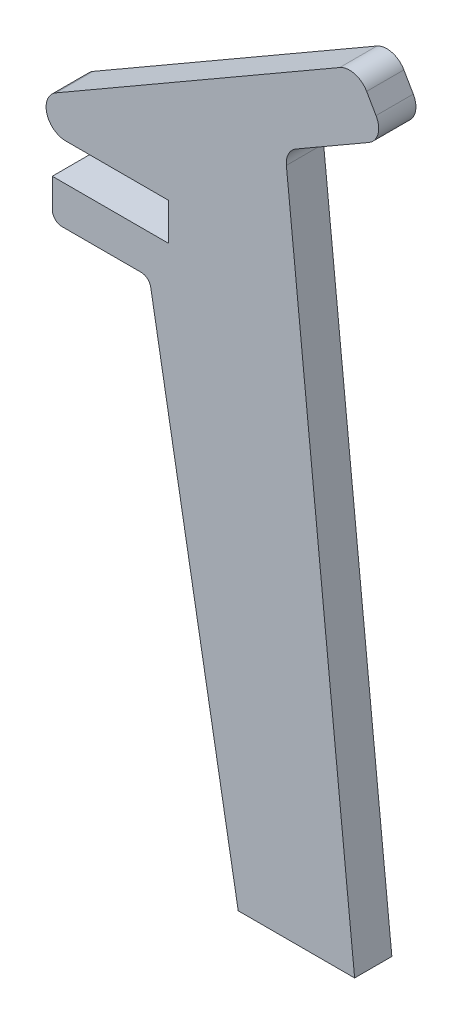
SolidWorks part; units mm, degrees
ref_plane "Front Plane" through (0, 0, 0) normal (0, 0, 1) x (1, 0, 0)
ref_plane "Top Plane" through (0, 0, 0) normal (0, 1, 0) x (1, 0, 0)
ref_plane "Right Plane" through (0, 0, 0) normal (1, 0, 0) x (0, 0, -1)
sketch "Sketch1" plane through (0, 0, 0) normal (0, 0, 1) x (1, 0, 0)
  line L0 (159.9956, -85.9179) -> (150.4706, -69.4202) construction
  line L1 (127, -104.9679) -> (159.9956, -85.9179) construction
  line L2 (150.4706, -69.4202) -> (31.146, -138.3122) construction
  line L3 (-88.9, -138.3122) -> (88.9, -138.3122) construction
  line L4 (88.9, -138.3122) -> (88.9, -150.5042) construction
  line L5 (-88.9, -150.5042) -> (88.9, -150.5042) construction
  line L6 (111.6616, -328.3042) -> (149.7616, -328.3042) construction
  line L8 (149.7616, -328.3042) -> (127, -104.9679) construction
  line L9 (159.9956, -85.9179) -> (150.4706, -69.4202)
  line L10 (127, -104.9679) -> (159.9956, -85.9179)
  line L11 (150.4706, -69.4202) -> (31.146, -138.3122)
  line L12 (31.146, -138.3122) -> (88.9, -138.3122)
  line L13 (88.9, -138.3122) -> (88.9, -150.5042)
  line L14 (50.8, -150.5042) -> (88.9, -150.5042)
  line L15 (111.6616, -328.3042) -> (149.7616, -328.3042)
  line L17 (149.7616, -328.3042) -> (127, -104.9679)
  line L18 (82.55, -163.2042) -> (111.6616, -328.3042) construction
  line L19 (50.8, -163.2042) -> (50.8, -150.5042) construction
  line L20 (82.55, -163.2042) -> (50.8, -163.2042) construction
  line L21 (82.55, -163.2042) -> (111.6616, -328.3042)
  line L22 (50.8, -163.2042) -> (50.8, -150.5042)
  line L23 (82.55, -163.2042) -> (50.8, -163.2042)
  point P11 (0, 0)
extrude "Boss-Extrude1" add sketch "Sketch1" along normal mid plane 12.192
fillet "Fillet1" radius 6.45 4 edges at (31.146, -138.3122, 0) (127, -104.9679, 0) (150.4706, -69.4202, 0) (159.9956, -85.9179, 0)
fillet "Fillet2" radius 3.175 2 edges at (82.55, -163.2042, 0) (50.8, -163.2042, 0)
